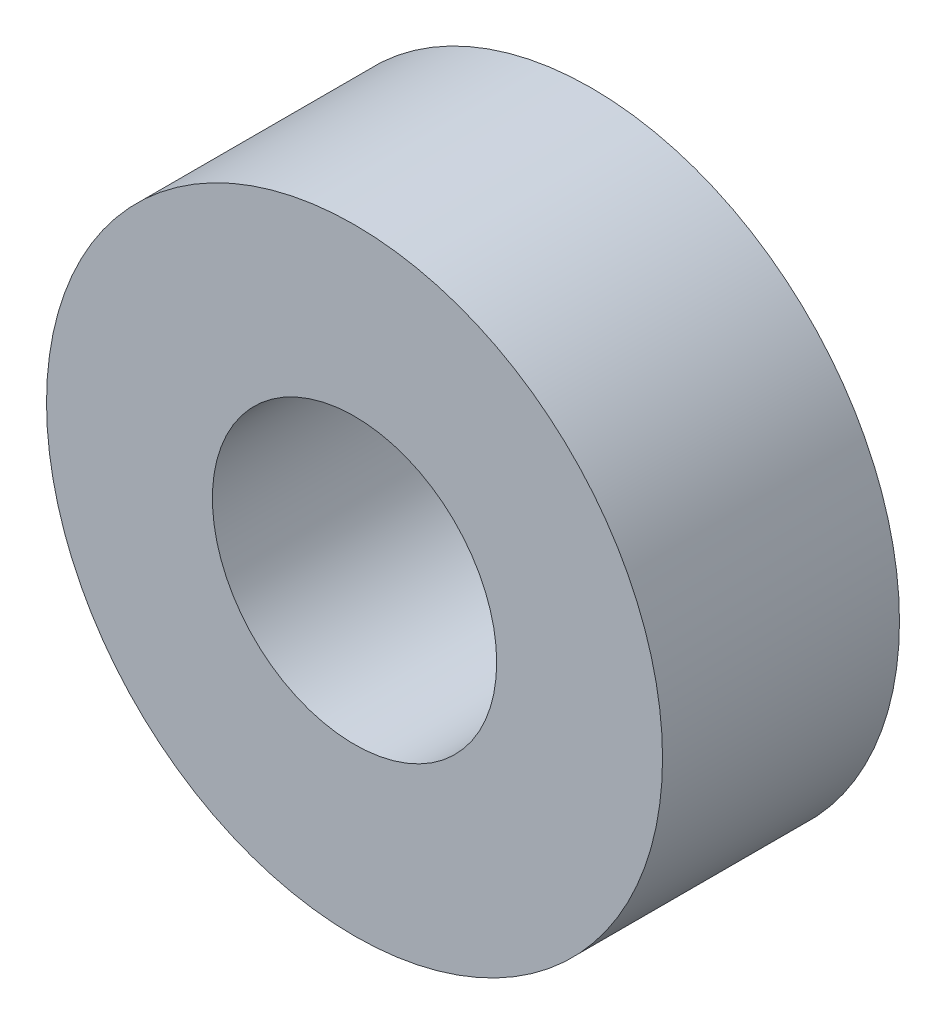
SolidWorks part; units mm, degrees
ref_plane "前视基准面" through (0, 0, 0) normal (0, 0, 1) x (1, 0, 0)
ref_plane "上视基准面" through (0, 0, 0) normal (0, 1, 0) x (1, 0, 0)
ref_plane "右视基准面" through (0, 0, 0) normal (1, 0, 0) x (0, 0, -1)
other "Configuration Table"
sketch "草图1" plane through (0, 0, 0) normal (0, 0, 1) x (1, 0, 0)
  circle A0 centre (0, 0) radius 6.5
  dimension "D1" = 13
extrude "凸台-拉伸1" add sketch "草图1" along normal blind 5
sketch "草图2" plane through (0, 0, 5) normal (0, 0, 1) x (1, 0, 0)
  circle A0 centre (0, 0) radius 3
  dimension "D1" = 6
extrude "切除-拉伸1" cut sketch "草图2" against normal blind 5
